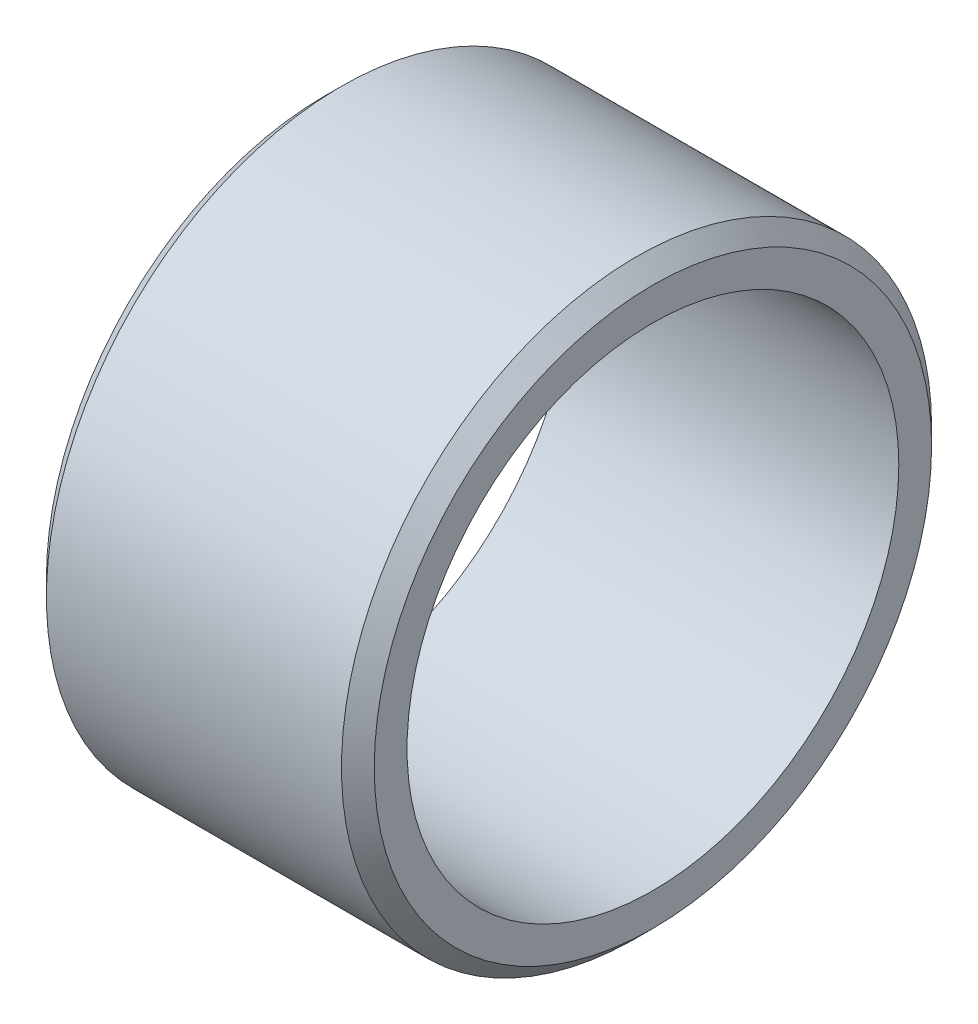
SolidWorks part; units mm, degrees
ref_plane "Front Plane" through (0, 0, 0) normal (0, 0, 1) x (1, 0, 0)
ref_plane "Top Plane" through (0, 0, 0) normal (0, 1, 0) x (1, 0, 0)
ref_plane "Right Plane" through (0, 0, 0) normal (1, 0, 0) x (0, 0, -1)
sketch "Sketch1" plane through (0, 0, 0) normal (0, 0, 1) x (1, 0, 0)
  line L0 (0, 8.5) -> (0, 7.5)
  line L1 (0, 7.5) -> (10, 7.5)
  line L2 (10, 7.5) -> (10, 8.5)
  line L3 (10, 8.5) -> (9.5, 9)
  line L4 (9.5, 9) -> (0.5, 9)
  line L5 (0.5, 9) -> (0, 8.5)
  line L6 (0, 0) -> (10, 0) construction
revolve "Revolve1" add sketch "Sketch1" angle 360 about L6
